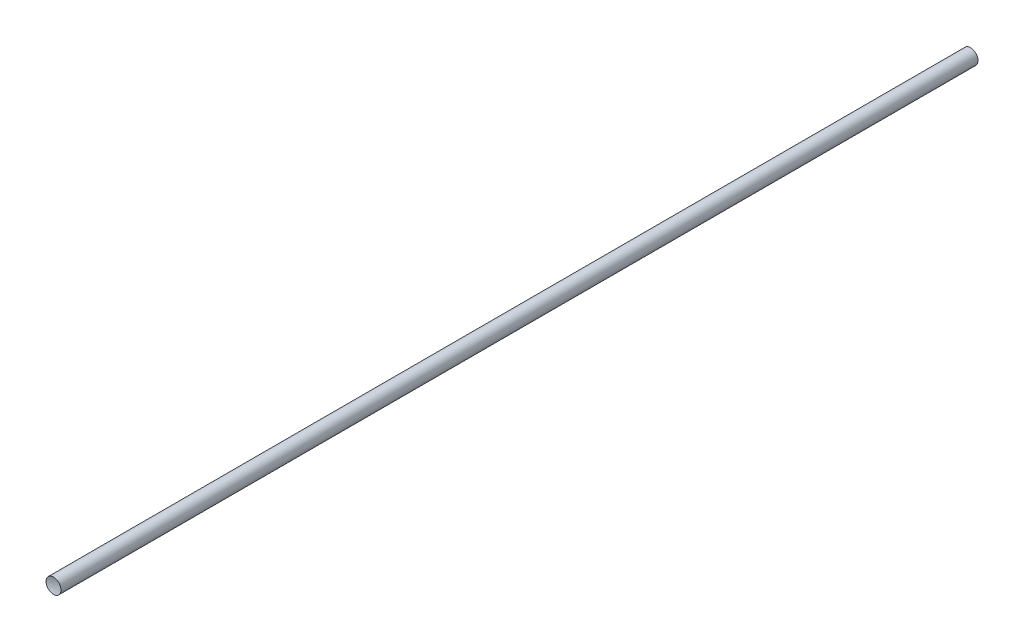
SolidWorks part; units mm, degrees
ref_plane "Plan de face" through (0, 0, 0) normal (0, 0, 1) x (1, 0, 0)
ref_plane "Plan de dessus" through (0, 0, 0) normal (0, 1, 0) x (1, 0, 0)
ref_plane "Plan de droite" through (0, 0, 0) normal (1, 0, 0) x (0, 0, -1)
sketch "Esquisse1" plane through (0, 0, 0) normal (0, 0, 1) x (1, 0, 0)
  circle A0 centre (0, 0) radius 2
  dimension "D1" = 4
extrude "Boss.-Extru.1" add sketch "Esquisse1" along normal mid plane 256.8
sketch "Esquisse2" plane through (0, 0, 0) normal (0, 1, 0) x (1, 0, 0)
  line L0 (2, 128.4) -> (-2, 128.4) construction
  line L1 (6.35, 128.4) -> (-6.35, 128.4) construction
  line L2 (6.35, 128.4) -> (-6.35, 128.4)
  arc A0 (-6.35, 128.4) -> (6.35, 128.4) centre (0, 128.4) ccw
  dimension "D1" = 12.7
revolve "Enlèvement de matière-Révolution1" cut sketch "Esquisse2" angle 360 about L1
mirror "Symétrie1" about plane through (0, 0, 0) normal (0, 0, 1) of "Enlèvement de matière-Révolution1"
